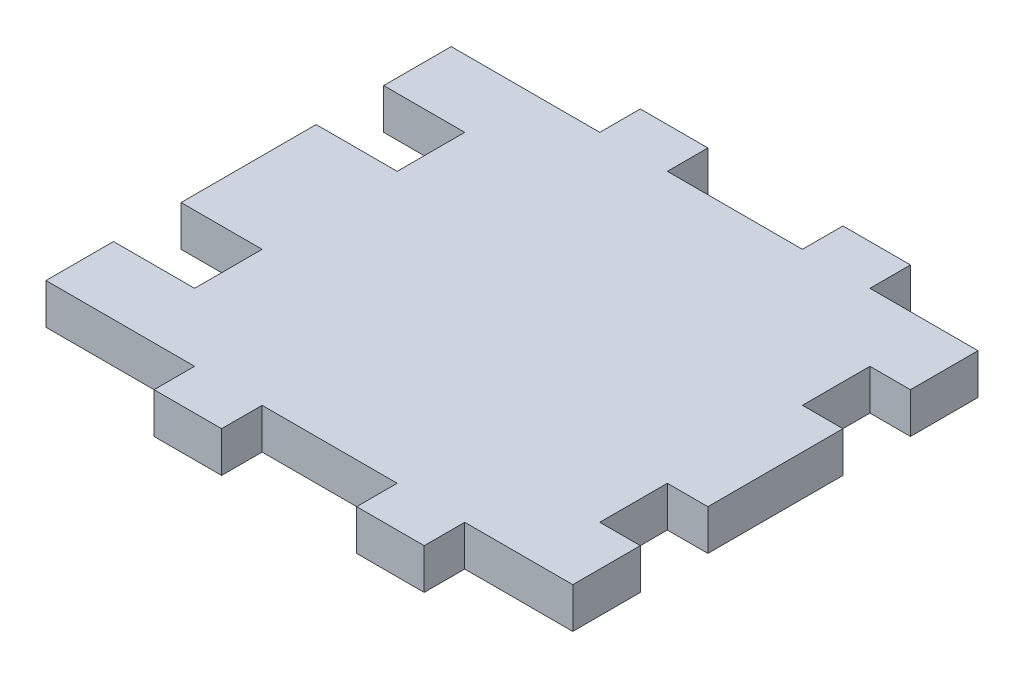
SolidWorks part; units mm, degrees
ref_plane "Front Plane" through (0, 0, 0) normal (0, 0, 1) x (1, 0, 0)
ref_plane "Top Plane" through (0, 0, 0) normal (0, 1, 0) x (1, 0, 0)
ref_plane "Right Plane" through (0, 0, 0) normal (1, 0, 0) x (0, 0, -1)
sketch "Sketch1" plane through (0, 0, 0) normal (0, 1, 0) x (1, 0, 0)
  line L0 (2.2355, 32.0745) -> (0, 30) construction
  line L1 (-30, 30) -> (30, 30)
  line L2 (-30, 30) -> (-30, -30)
  line L3 (-30, -30) -> (30, -30)
  line L4 (30, 30) -> (30, -30)
  line L5 (-30, 30) -> (30, -30) construction
  line L6 (-30, -30) -> (30, 30) construction
  line L7 (0, 30) -> (0, -30) construction
  line L8 (-30, 0) -> (30, 0) construction
  line L9 (10, -30) -> (10, -36)
  line L10 (-20, -30) -> (-10, -30)
  line L11 (-20, -30) -> (-20, -36)
  line L12 (-20, -36) -> (-10, -36)
  line L13 (-10, -30) -> (-10, -36)
  line L14 (20, -36) -> (10, -36)
  line L15 (20, -30) -> (20, -36)
  line L16 (20, -30) -> (10, -30)
  line L17 (-42, 30) -> (-42, 20)
  line L18 (-30, -30) -> (-42, -30)
  line L19 (-30, -30) -> (-30, -20)
  line L20 (-30, -20) -> (-42, -20)
  line L21 (-42, -30) -> (-42, -20)
  line L22 (-30, 20) -> (-42, 20)
  line L23 (-30, 30) -> (-30, 20)
  line L24 (-30, 30) -> (-42, 30)
  line L25 (-10, 30) -> (-10, 36)
  line L26 (20, 30) -> (10, 30)
  line L27 (20, 30) -> (20, 36)
  line L28 (20, 36) -> (10, 36)
  line L29 (10, 30) -> (10, 36)
  line L30 (-20, 36) -> (-10, 36)
  line L31 (-20, 30) -> (-20, 36)
  line L32 (-20, 30) -> (-10, 30)
  line L34 (-30, 10) -> (-42, 10)
  line L35 (-30, 10) -> (-30, -10)
  line L36 (-30, -10) -> (-42, -10)
  line L37 (-42, 10) -> (-42, -10)
  line L38 (30, -30) -> (36, -30)
  line L39 (30, -30) -> (30, -20)
  line L40 (30, -20) -> (36, -20)
  line L41 (30, -20) -> (36, -20) [skipped]
  line L42 (30, -10) -> (36, -10) [skipped]
  line L43 (36, -20) -> (36, -10) [skipped]
  line L44 (30, 10) -> (36, 10) [skipped]
  line L45 (30, 20) -> (36, 20) [skipped]
  line L46 (36, 20) -> (36, 10) [skipped]
  line L47 (-30, -10) -> (-36, -10) [skipped]
  line L48 (-36, -20) -> (-36, -10) [skipped]
  line L49 (-30, -20) -> (-36, -20) [skipped]
  line L50 (-36, 20) -> (-36, 10) [skipped]
  line L51 (-30, 20) -> (-36, 20) [skipped]
  line L52 (-30, 10) -> (-36, 10) [skipped]
  line L53 (36, -30) -> (36, -20)
  line L54 (-30, 20) -> (-30, 10) [skipped]
  line L55 (-30, -20) -> (-30, -10) [skipped]
  line L56 (30, -20) -> (30, -10) [skipped]
  line L57 (30, 20) -> (30, 10) [skipped]
  line L58 (30, -10) -> (36, -10)
  line L59 (30, -10) -> (30, 10)
  line L60 (30, 10) -> (36, 10)
  line L61 (36, -10) -> (36, 10)
  line L62 (30, 30) -> (36, 30)
  line L63 (30, 30) -> (30, 20)
  line L64 (30, 20) -> (36, 20)
  line L65 (30, 30) -> (30, -30)
  line L66 (36, 30) -> (36, 20)
  point P0 (0, 0)
  point P29 (-36, -10)
  point P46 (0, 0)
  dimension "D1" = 60
  dimension "D2" = 60
  dimension "D3" = 12
  dimension "D4" = 10
  dimension "D5" = 4
  dimension "D6" = 10
  dimension "D7" = 10
  dimension "D8" = 20
  dimension "D9" = 12
  dimension "D10" = 6
extrude "Boss-Extrude1" add sketch "Sketch1" along normal blind 6
